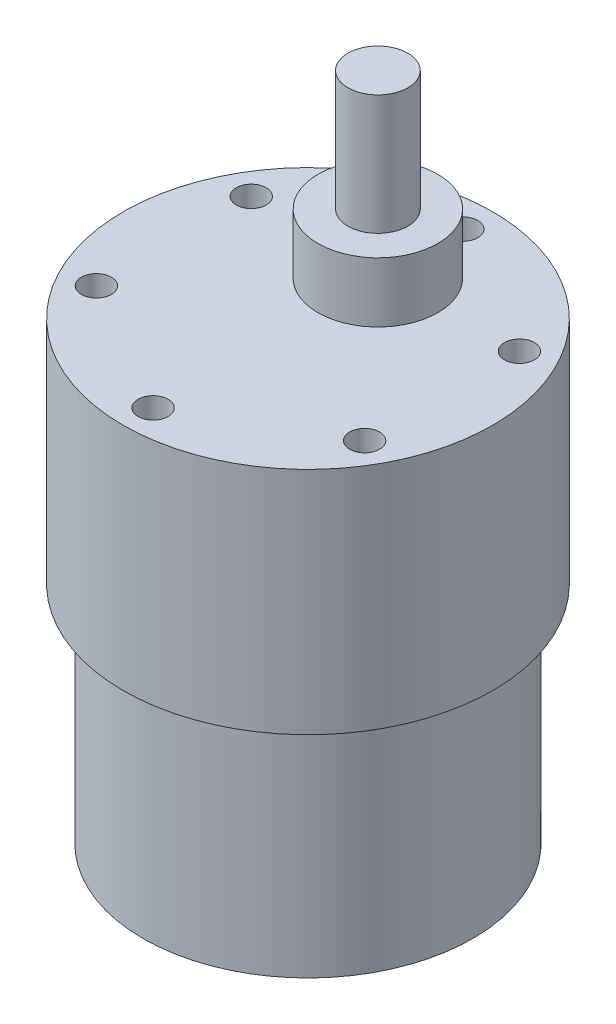
SolidWorks part; units mm, degrees
ref_plane "前视基准面" through (0, 0, 0) normal (0, 0, 1) x (1, 0, 0)
ref_plane "上视基准面" through (0, 0, 0) normal (0, 1, 0) x (1, 0, 0)
ref_plane "右视基准面" through (0, 0, 0) normal (1, 0, 0) x (0, 0, -1)
sketch "草图1" plane through (0, 0, 0) normal (0, 1, 0) x (1, 0, 0)
  circle A0 centre (0, 0) radius 18.5
  dimension "D1" = 37
extrude "凸台-拉伸1" add sketch "草图1" against normal blind 23
sketch "草图3" plane through (0, -23, 0) normal (0, -1, 0) x (1, 0, 0)
  circle A0 centre (0, 0) radius 16.5
  dimension "D1" = 33
extrude "凸台-拉伸2" add sketch "草图3" along normal blind 22.5
sketch "草图4" plane through (0, 0, 0) normal (0, 1, 0) x (1, 0, 0)
  circle A0 centre (0, 0) radius 15.5 construction
  circle A1 centre (0, 15.5) radius 1.5
  circle A2 centre (13.4234, 7.75) radius 1.5
  circle A3 centre (13.4234, -7.75) radius 1.5
  circle A4 centre (0, -15.5) radius 1.5
  circle A5 centre (-13.4234, -7.75) radius 1.5
  circle A6 centre (-13.4234, 7.75) radius 1.5
  point P17 (0, 0)
  dimension "D1" = 31
  dimension "D2" = 3
  dimension "D3" = 6
extrude "切除-拉伸1" cut sketch "草图4" against normal blind 15
sketch "草图5" plane through (0, 0, 0) normal (0, 1, 0) x (1, 0, 0)
  circle A0 centre (0, 7) radius 6
  point P2 (0, 0)
  dimension "D1" = 12
  dimension "D2" = 7
extrude "凸台-拉伸3" add sketch "草图5" along normal blind 6
sketch "草图6" plane through (0, 6, 0) normal (0, 1, 0) x (1, 0, 0)
  circle A0 centre (0, 7) radius 3
  circle A1 centre (0, 7) radius 6 construction
  dimension "D1" = 6
extrude "凸台-拉伸4" add sketch "草图6" along normal blind 12
